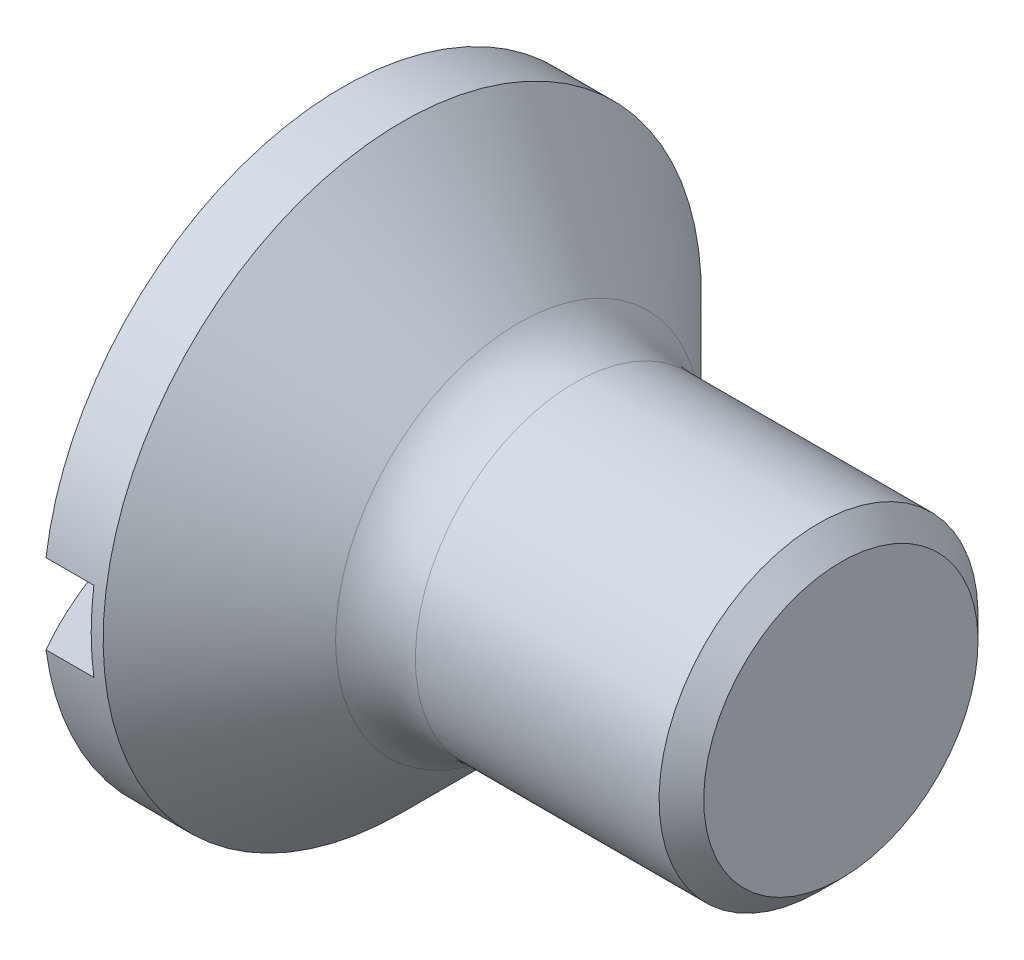
SolidWorks part; units mm, degrees
ref_plane "Přední rovina" through (0, 0, 0) normal (0, 0, 1) x (1, 0, 0)
ref_plane "Vrchní rovina" through (0, 0, 0) normal (0, 1, 0) x (1, 0, 0)
ref_plane "Pravá rovina" through (0, 0, 0) normal (1, 0, 0) x (0, 0, -1)
sketch "Skica1" plane through (0, 0, 0) normal (0, 0, 1) x (1, 0, 0)
  line L0 (0, 0) -> (2.9, 0) construction
  line L1 (0.4, 1.5) -> (0.7, 1.5)
  line L2 (0.7, 1.5) -> (1.4, 0.8)
  line L3 (1.4, 0.8) -> (2.9, 0.8)
  line L4 (2.9, 0.8) -> (2.9, 0)
  line L5 (2.9, 0) -> (0, 0)
  arc A0 (0, 0) -> (0.4, 1.5) centre (3.0125, 0) cw
  dimension "M" = 1.6
  dimension "l" = 2.5
  dimension "D3" = 45
  dimension "f" = 0.4
  dimension "D" = 3
  dimension "k" = 1
revolve "Otočit kolem osy1" add sketch "Skica1" angle 360 about L0
cosmetic thread "Kosmetický závit1" parameters "D1"=1.33, "D2"=1.36
ref_plane "Rovina1" through (0.64, 0, 0) normal (1, 0, 0) x (0, 0, -1)
sketch "Skica2" plane through (0.64, 0, 0) normal (1, 0, 0) x (0, 0, -1)
  line L0 (0, 0.2) -> (0, 0) construction
  line L1 (1.5, 0.2) -> (-1.5, 0.2)
  line L2 (1.5, 0.2) -> (1.5, -0.2)
  line L3 (1.5, -0.2) -> (-1.5, -0.2)
  line L4 (-1.5, 0.2) -> (-1.5, -0.2)
  line L5 (0, 0) -> (-1.5, 0) construction
  circle A0 centre (0, 0) radius 1.5 construction
  dimension "D1" = 0.4
extrude "Odebrat vysunutím1" cut sketch "Skica2" against normal through all
fillet "Zaoblit1" radius 0.4 1 edges at (1.4, -0.8, 0)
chamfer "Zkosit1" distance 0.112 angle 45 1 edges at (2.9, -0.8, 0)
equation "\"D1@Zkosit1\" = 0.07 * \"M@Skica1\""
equation "\"D2@Kosmetický závit1\" = 0.85 * \"M@Skica1\""
